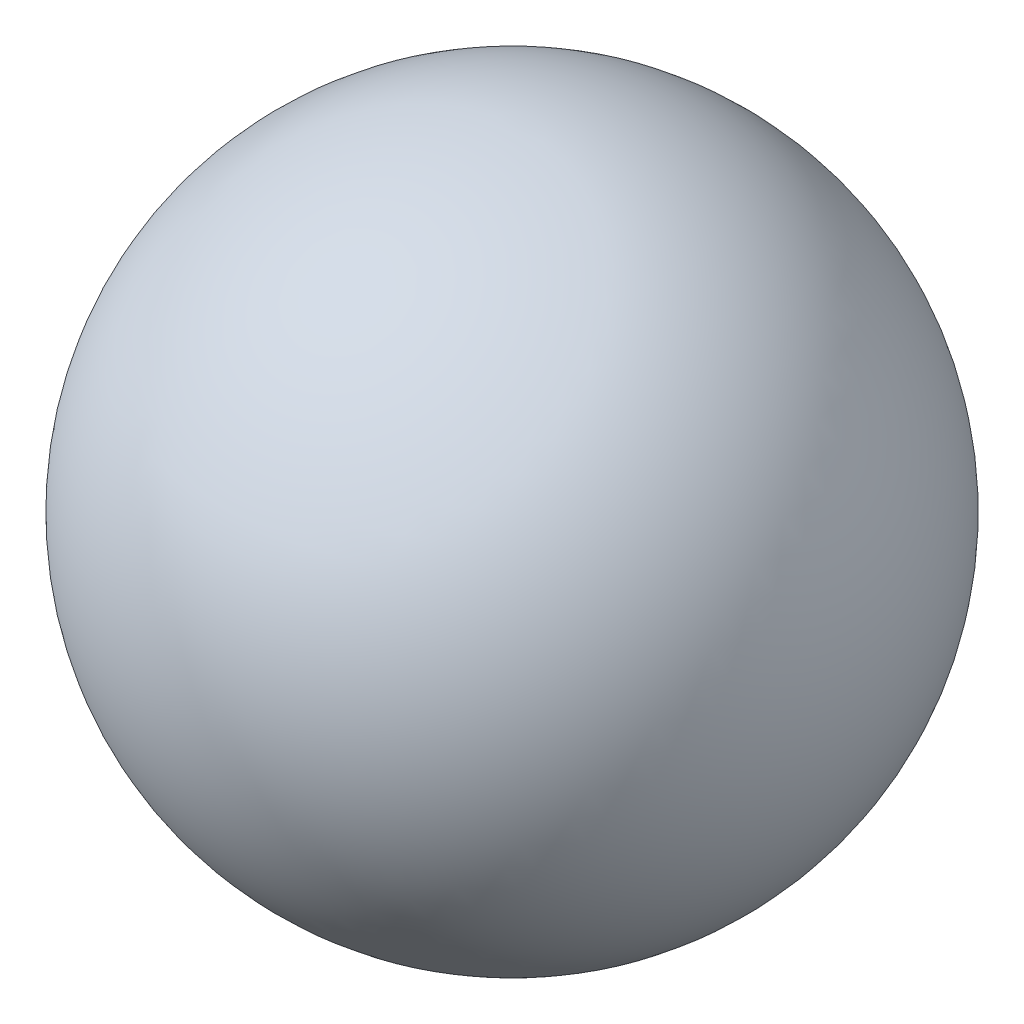
SolidWorks part; units mm, degrees
ref_plane "Front Plane" through (0, 0, 0) normal (0, 0, 1) x (1, 0, 0)
ref_plane "Top Plane" through (0, 0, 0) normal (0, 1, 0) x (1, 0, 0)
ref_plane "Right Plane" through (0, 0, 0) normal (1, 0, 0) x (0, 0, -1)
sketch "Sketch1" plane through (0, 0, 0) normal (1, 0, 0) x (0, 0, -1)
  line L0 (0, -12) -> (0, 12)
  arc A3 (0, 12) -> (0, -12) centre (0, 0) cw
  point P4 (0, 0)
  dimension "D2" = 12
  dimension "D1" = 24
revolve "Revolve5" add sketch "Sketch1" angle 360 about L0
